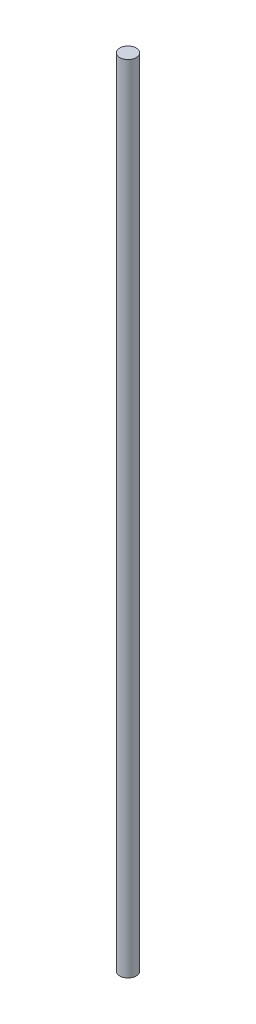
SolidWorks part; units mm, degrees
ref_plane "Front Plane" through (0, 0, 0) normal (0, 0, 1) x (1, 0, 0)
ref_plane "Top Plane" through (0, 0, 0) normal (0, 1, 0) x (1, 0, 0)
ref_plane "Right Plane" through (0, 0, 0) normal (1, 0, 0) x (0, 0, -1)
sketch "Sketch2" plane through (0, 0, 0) normal (0, 1, 0) x (1, 0, 0)
  circle A0 centre (-66.8787, 2.2607) radius 3.175
  dimension "D1" = 6.35
extrude "Boss-Extrude2" add sketch "Sketch2" along normal blind 304.8
